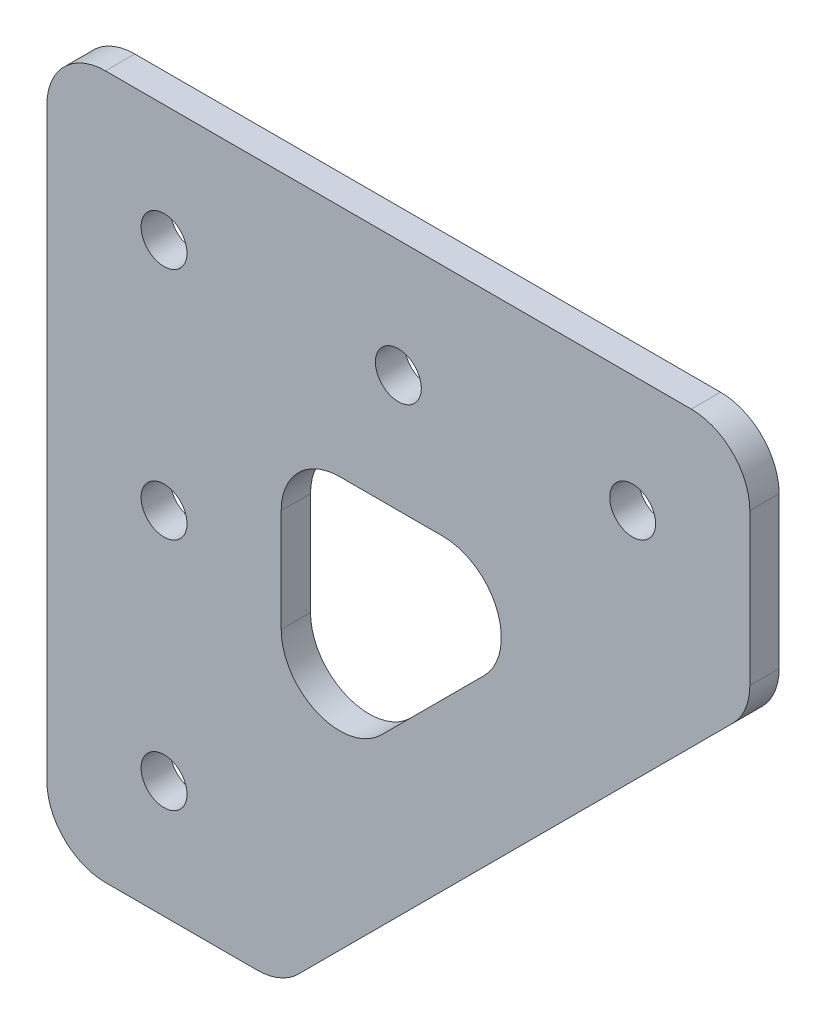
SolidWorks part; units mm, degrees
material "6061-T6 (SS)"
ref_plane "Front Plane" through (0, 0, 0) normal (0, 0, 1) x (1, 0, 0)
ref_plane "Top Plane" through (0, 0, 0) normal (0, 1, 0) x (1, 0, 0)
ref_plane "Right Plane" through (0, 0, 0) normal (1, 0, 0) x (0, 0, -1)
sketch "Sketch1" plane through (0, 0, 0) normal (0, 0, 1) x (1, 0, 0)
  line L0 (0, 0) -> (0, 76.2)
  line L9 (0, 76.2) -> (76.2, 76.2)
  line L10 (76.2, 76.2) -> (76.2, 50.8)
  line L11 (58.2395, 50.8) -> (25.4, 50.8)
  line L12 (25.4, 50.8) -> (25.4, 17.9605)
  line L13 (25.4, 0) -> (0, 0)
  line L14 (25.4, 0) -> (76.2, 50.8)
  line L15 (58.2395, 50.8) -> (25.4, 17.9605)
  dimension "D1" = 25.4
  dimension "D2" = 25.4
  dimension "D3" = 76.2
  dimension "D4" = 76.2
  dimension "D5" = 12.7
extrude "Boss-Extrude1" add sketch "Sketch1" against normal blind 3.175 contours L13 L14 L10 L9 L0 L11 L15 L12
sketch "Sketch2" plane through (0, 0, 0) normal (0, 0, 1) x (1, 0, 0)
  line L0 (0, 76.2) -> (76.2, 76.2) construction
  line L1 (0, 0) -> (0, 76.2) construction
  circle A0 centre (12.7, 63.5) radius 2.4892
  circle A1 centre (38.1, 63.5) radius 2.4892
  circle A2 centre (63.5, 63.5) radius 2.4892
  circle A3 centre (12.7, 38.1) radius 2.4892
  circle A4 centre (12.7, 12.7) radius 2.4892
  dimension "D3" = 4.9784
  dimension "D1" = 12.7
  dimension "D2" = 12.7
  dimension "D4" = 3
  dimension "D5" = 3
extrude "Cut-Extrude1" cut sketch "Sketch2" against normal through all
fillet "Fillet3" radius 6.35 8 edges at (58.2395, 50.8, -1.5875) (25.4, 17.9605, -1.5875) (25.4, 50.8, -1.5875) (25.4, 0, -1.5875) (76.2, 50.8, -1.5875) (76.2, 76.2, -1.5875) (0, 0, -1.5875) (0, 76.2, -1.5875)
